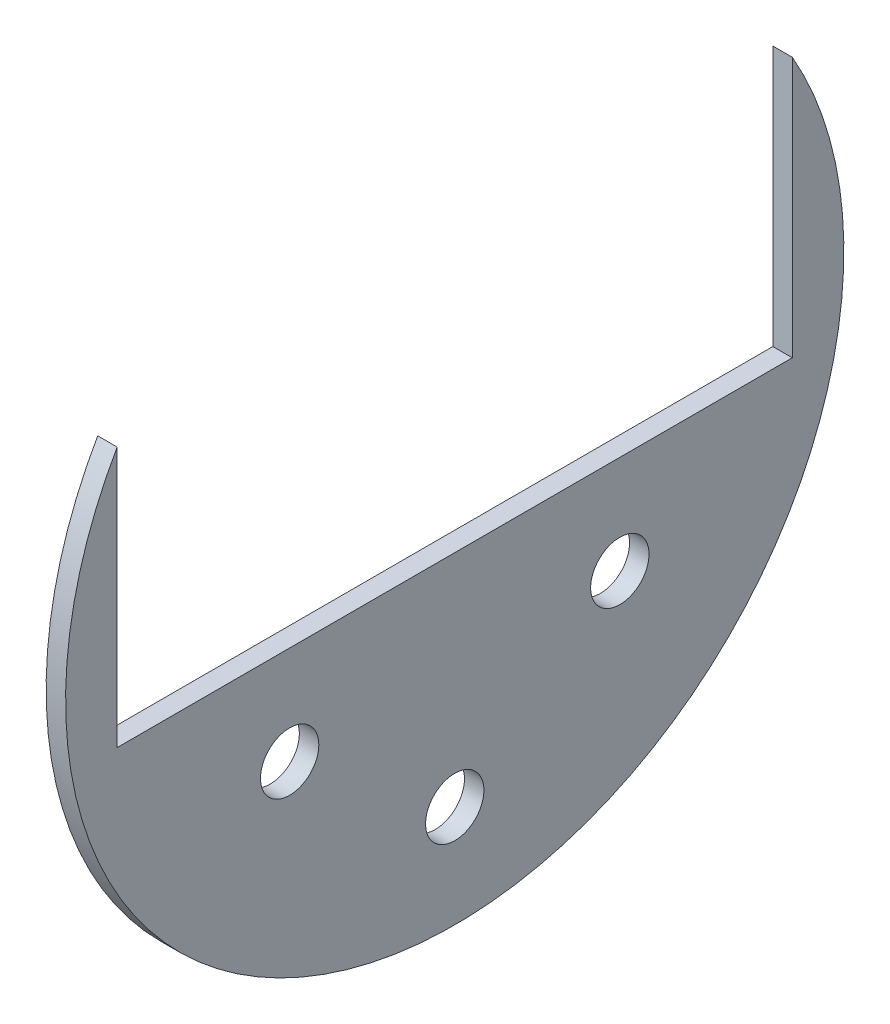
SolidWorks part; units mm, degrees
ref_plane "Front Plane" through (0, 0, 0) normal (0, 0, 1) x (1, 0, 0)
ref_plane "Top Plane" through (0, 0, 0) normal (0, 1, 0) x (1, 0, 0)
ref_plane "Right Plane" through (0, 0, 0) normal (1, 0, 0) x (0, 0, -1)
sketch "Sketch1" plane through (0, 0, 0) normal (1, 0, 0) x (0, 0, -1)
  line L0 (0, 0) -> (0, 14.75) construction
  line L1 (0, 14.75) -> (-8.4853, 8.4853) construction
  line L2 (-8.4853, 8.4853) -> (-14.75, 0) construction
  line L3 (0, 0) -> (-8.4853, 8.4853) construction
  circle A0 centre (0, 0) radius 20
  circle A1 centre (0, 0) radius 14.75
  circle A2 centre (0, 0) radius 12
  circle A3 centre (0, 14.75) radius 1.5
  circle A4 centre (14.75, 0) radius 1.5
  circle A5 centre (0, -14.75) radius 1.5
  circle A6 centre (-14.75, 0) radius 1.5
  circle A7 centre (-8.4853, 8.4853) radius 1.5
  circle A8 centre (8.4853, 8.4853) radius 1.5
  circle A9 centre (8.4853, -8.4853) radius 1.5
  circle A10 centre (-8.4853, -8.4853) radius 1.5
  dimension "D1" = 29.5
  dimension "D2" = 40
  dimension "D3" = 24
  dimension "D4" = 4
  dimension "D6" = 4
  dimension "D5" = 14.75
  dimension "D7" = 12
extrude "Boss-Extrude1" add sketch "Sketch1" along normal blind 1 contours A0 A6 A1 A3 A4 A5 | A6 A1 A5 A4 A3 A10 A2 A7 A8 A9 | A10 A2 A9 A8 A7
sketch "Sketch3" plane through (1, 0, 0) normal (1, 0, 0) x (0, 0, -1)
  line L4 (-16.75, 16.75) -> (-16.75, -2.8284)
  line L5 (-16.75, -2.8284) -> (16.75, -2.8284)
  line L6 (16.75, -2.8284) -> (16.75, 16.75)
  line L7 (16.75, 16.75) -> (-16.75, 16.75)
  line L8 (-16.75, 16.75) -> (-16.75, -2.8284) construction
  line L9 (-16.75, -2.8284) -> (16.75, -2.8284) construction
  line L10 (16.75, -2.8284) -> (16.75, 16.75) construction
  line L11 (16.75, 16.75) -> (-16.75, 16.75) construction
  line L16 (-17.35, 17.35) -> (-17.35, -3.4284)
  line L17 (-17.35, -3.4284) -> (17.35, -3.4284)
  line L18 (17.35, -3.4284) -> (17.35, 17.35)
  line L19 (17.35, 17.35) -> (-17.35, 17.35)
  line L20 (-17.35, 17.35) -> (-17.35, -3.4284)
  line L21 (-17.35, -3.4284) -> (17.35, -3.4284)
  line L22 (17.35, -3.4284) -> (17.35, 17.35)
  line L23 (17.35, 17.35) -> (-17.35, 17.35)
  dimension "D1" = 0
  dimension "D2" = 0.6
extrude "Cut-Extrude1" cut sketch "Sketch3" against normal through all
